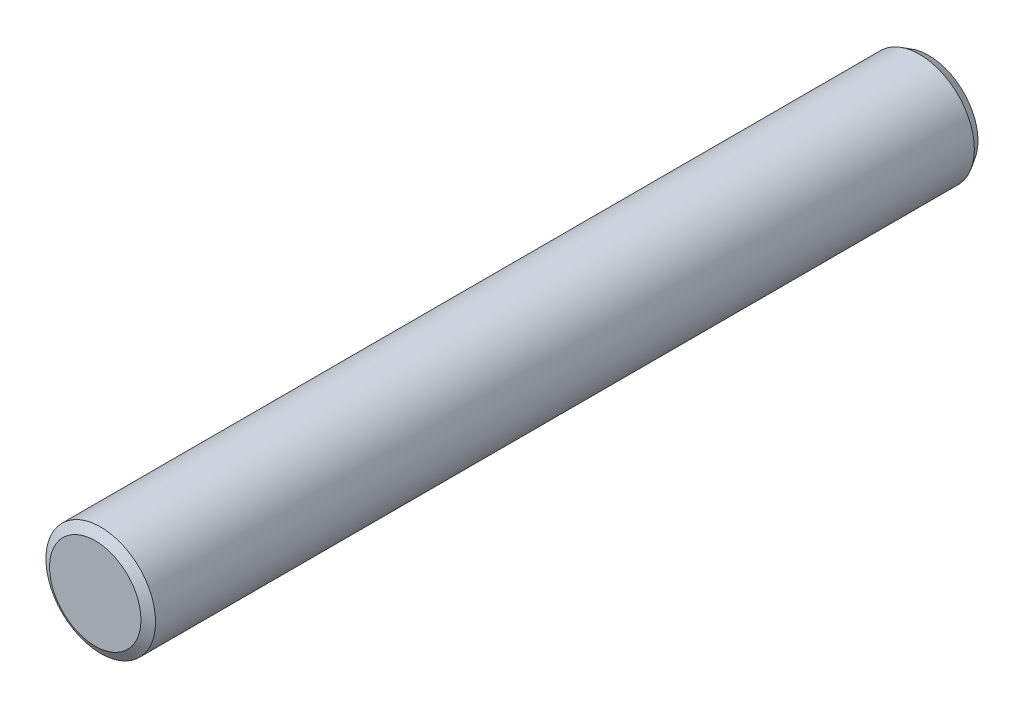
SolidWorks part; units mm, degrees
ref_plane "Piano frontale" through (0, 0, 0) normal (0, 0, 1) x (1, 0, 0)
ref_plane "Piano superiore" through (0, 0, 0) normal (0, 1, 0) x (1, 0, 0)
ref_plane "Piano destro" through (0, 0, 0) normal (1, 0, 0) x (0, 0, -1)
sketch "Schizzo1" plane through (0, 0, 0) normal (0, 0, 1) x (1, 0, 0)
  circle A0 centre (0, 0) radius 5
  dimension "D1" = 10
extrude "Estrusione-Estrusione1" add sketch "Schizzo1" along normal blind 76
cosmetic thread "Filettatura cosmetica2" parameters "D1"=32, "D2"=9.387
cosmetic thread "Filettatura cosmetica3" parameters "D1"=18, "D2"=9.387
chamfer "Smusso1" distance 0.5 angle 59 2 edges at (5, 0, 0) (5, 0, 76)
